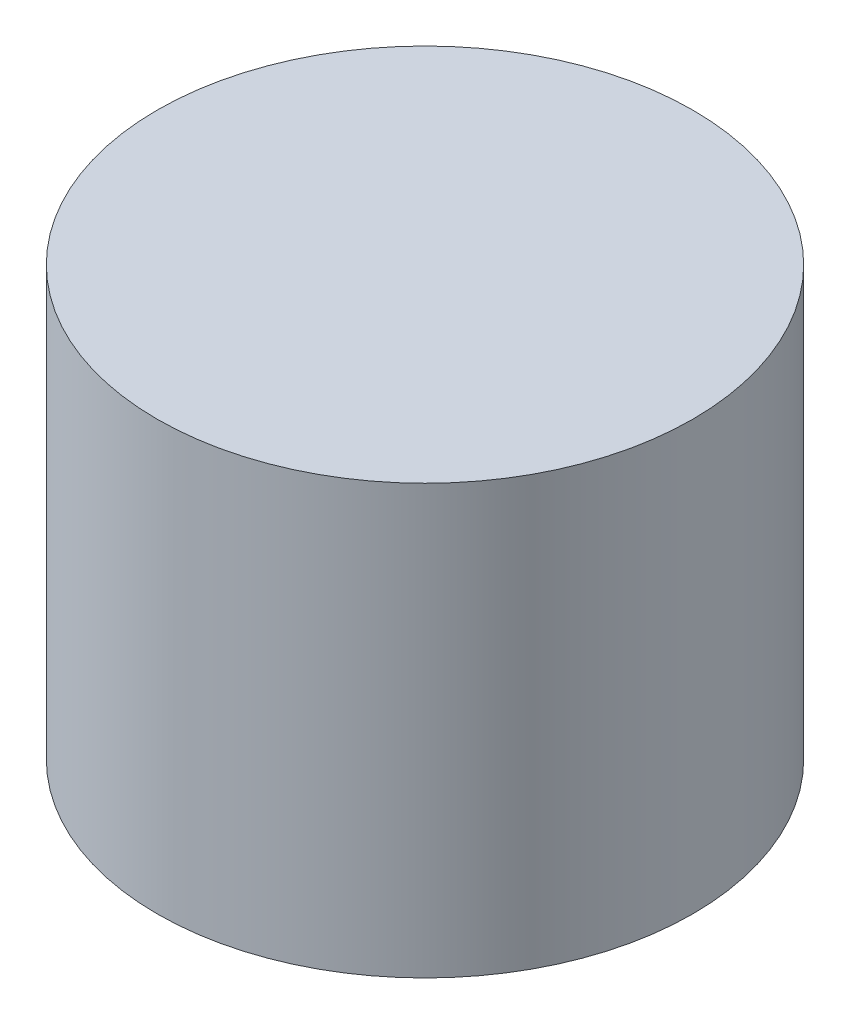
SolidWorks part; units mm, degrees
ref_plane "Front Plane" through (0, 0, 0) normal (0, 0, 1) x (1, 0, 0)
ref_plane "Top Plane" through (0, 0, 0) normal (0, 1, 0) x (1, 0, 0)
ref_plane "Right Plane" through (0, 0, 0) normal (1, 0, 0) x (0, 0, -1)
sketch "Sketch1" plane through (0, 0, 0) normal (0, 1, 0) x (1, 0, 0)
  circle A0 centre (-12.667, -5.8557) radius 12.5
  dimension "D1" = 25
extrude "Boss-Extrude1" add sketch "Sketch1" along normal blind 20
